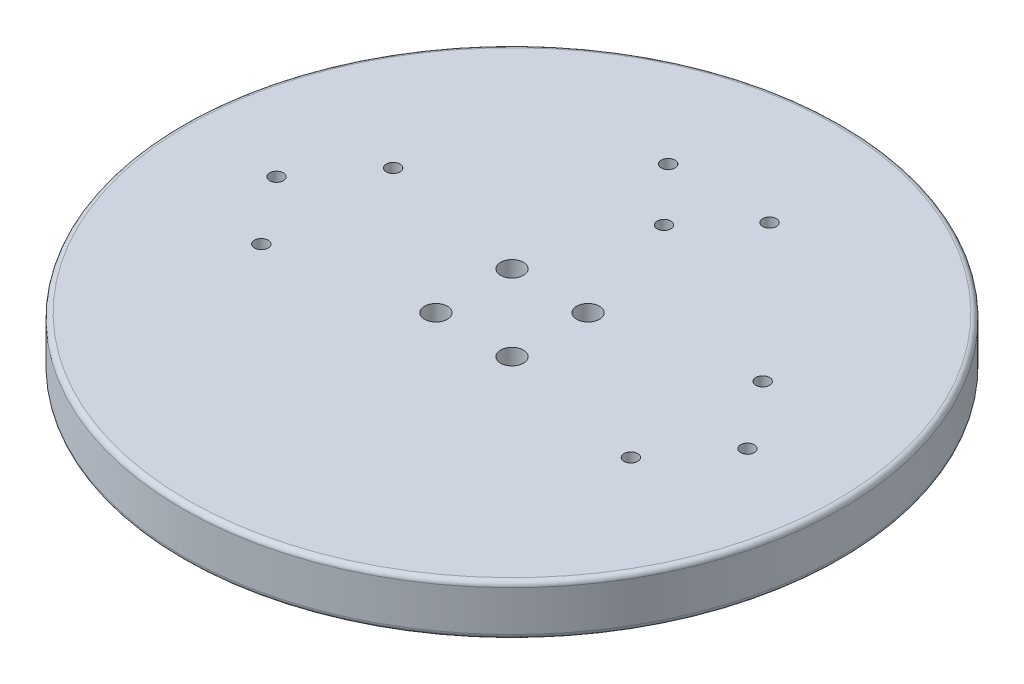
SolidWorks part; units mm, degrees
material "Delrin 2700 NC010, Low Viscosity Acetal Copolymer (SS)"
ref_plane "Front Plane" through (0, 0, 0) normal (0, 0, 1) x (1, 0, 0)
ref_plane "Top Plane" through (0, 0, 0) normal (0, 1, 0) x (1, 0, 0)
ref_plane "Right Plane" through (0, 0, 0) normal (1, 0, 0) x (0, 0, -1)
sketch "Sketch1" plane through (0, 0, 0) normal (0, 1, 0) x (1, 0, 0)
  circle A0 centre (0, 0) radius 65
  dimension "D1" = 130
extrude "Boss-Extrude1" add sketch "Sketch1" along normal blind 10
fillet "Fillet1" radius 1 2 edges at (0, 0, 65) (0, 10, 65)
hole_wizard "#6-32 Tapped Hole1" positions "Sketch2" profile "Sketch3" tap size "#6-32" standard "ANSI Inch" end condition through all
sketch "Sketch2" plane through (0, 0, 0) normal (0, 1, 0) x (1, 0, 0)
  point P0 (-46.445, 0)
  point P2 (46.445, 0)
  point P4 (-36.445, 13)
  point P6 (-36.445, -13)
  point P8 (36.445, -13)
  point P10 (36.445, 13)
  point P28 (0, 29.98)
  point P30 (-10, 40.8)
  point P32 (10, 40.8)
  dimension "D1" = 46.445
  dimension "D2" = 46.445
  dimension "D3" = 36.445
  dimension "D4" = 36.445
  dimension "D5" = 13
  dimension "D6" = 13
  dimension "D7" = 29.98
  dimension "D8" = 10.82
  dimension "D9" = 20
  dimension "D10" = 10
sketch "Sketch3" plane through (-46.445, 0, 0) normal (1, 0, 0) x (0, 0, -1)
  line L0 (0, 0) -> (0, 10)
  line L1 (0, 10) -> (1.3525, 10)
  line L2 (1.3525, 10) -> (1.3525, 0)
  line L5 (1.3525, 0) -> (0, 0)
  line L11 (0, -6.35) -> (0, 107.95) construction
  dimension "Thru Tap Drill Dia." = 2.7051
  dimension "Thru Tap Drill Depth" = 10
cosmetic thread "Hole Thread1" parameters "D2"=3.5052
cosmetic thread "Hole Thread2" parameters "D2"=3.5052
cosmetic thread "Hole Thread3" parameters "D2"=3.5052
cosmetic thread "Hole Thread4" parameters "D2"=3.5052
cosmetic thread "Hole Thread5" parameters "D2"=3.5052
cosmetic thread "Hole Thread6" parameters "D2"=3.5052
cosmetic thread "Hole Thread9" parameters "D2"=3.5052
cosmetic thread "Hole Thread10" parameters "D2"=3.5052
cosmetic thread "Hole Thread11" parameters "D2"=3.5052
hole_wizard "#4-40 Tapped Hole1" [suppressed] positions "Sketch5" profile "Sketch6" tap size "#4-40" standard "ANSI Inch"
sketch "Sketch5" plane through (0, 0, 0) normal (0, -1, 0) x (-1, 0, 0)
  circle A0 centre (-36.145, 0) radius 1.3526 construction
  point P0 (-48.145, 27.124)
  point P2 (-48.145, -27.124)
  dimension "D1" = 12
  dimension "D2" = 27.124
  dimension "D3" = 27.124
sketch "Sketch6" plane through (48.145, 0, -27.124) normal (1, 0, 0) x (0, 0, -1)
  line L0 (0, 0) -> (0, 25.4)
  line L1 (0, 25.4) -> (1.1303, 25.4)
  line L2 (1.1303, 25.4) -> (1.1303, 0)
  line L5 (1.1303, 0) -> (0, 0)
  line L11 (0, -6.35) -> (0, 107.95) construction
  dimension "Thru Tap Drill Dia." = 2.2606
  dimension "Thru Tap Drill Depth" = 25.4
cosmetic thread "Hole Thread7" [suppressed] parameters "D2"=2.8448
cosmetic thread "Hole Thread8" [suppressed] parameters "D2"=2.8448
hole_wizard "#8 Clearance Hole1" positions "Sketch7" profile "Sketch8" hole size "#8" standard "ANSI Inch" end condition through all
sketch "Sketch7" plane through (0, 0, 0) normal (0, -1, 0) x (-1, 0, 0)
  circle A0 centre (0, 0) radius 16.5 construction
  point P0 (7.5, -7.5)
  point P2 (-7.5, -7.5)
  point P4 (7.5, 7.5)
  point P6 (-7.5, 7.5)
  dimension "D5" = 33
  dimension "D1" = 7.5
  dimension "D2" = 7.5
  dimension "D3" = 7.5
  dimension "D4" = 7.5
sketch "Sketch8" plane through (-7.5, 0, 7.5) normal (1, 0, 0) x (0, 0, -1)
  line L0 (0, 0) -> (0, 10)
  line L1 (0, 10) -> (2.2479, 10)
  line L2 (2.2479, 10) -> (2.2479, 0)
  line L5 (2.2479, 0) -> (0, 0)
  line L11 (0, -6.35) -> (0, 107.95) construction
  dimension "Thru Hole Dia." = 4.4958
  dimension "Thru Hole Depth" = 10
equation "\"D2@Sketch2\"=\"D1@Sketch2\""
equation "\"D4@Sketch2\"=\"D3@Sketch2\""
equation "\"D6@Sketch2\"=\"D5@Sketch2\""
equation "\"D2@Sketch5\"=\"D3@Sketch5\""
equation "\"D2@Sketch7\"=\"D1@Sketch7\""
equation "\"D3@Sketch7\"=\"D4@Sketch7\""
equation "\"D1@Sketch2\"=92.89/2"
equation "\"D3@Sketch2\"=72.89/2"
equation "\"D10@Sketch2\"=\"D9@Sketch2\"/2"
